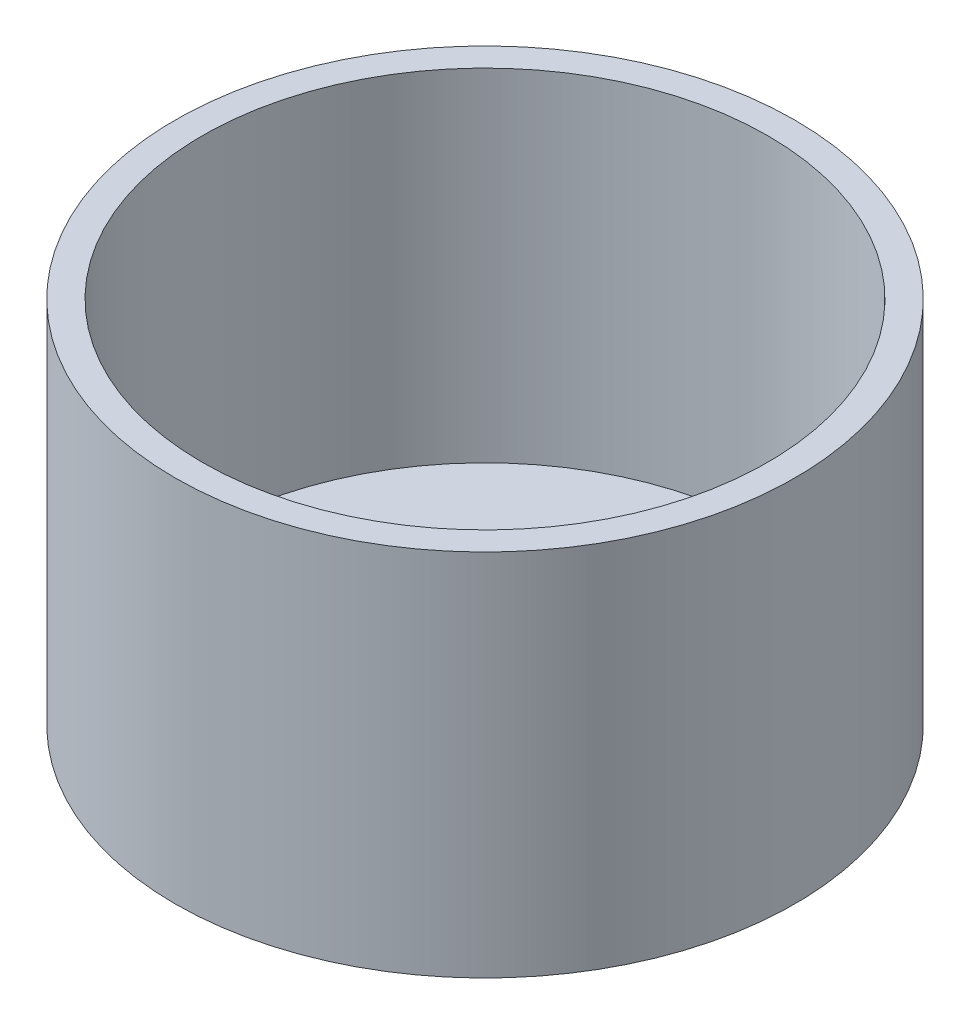
SolidWorks part; units mm, degrees
ref_plane "前视基准面" through (0, 0, 0) normal (0, 0, 1) x (1, 0, 0)
ref_plane "上视基准面" through (0, 0, 0) normal (0, 1, 0) x (1, 0, 0)
ref_plane "右视基准面" through (0, 0, 0) normal (1, 0, 0) x (0, 0, -1)
sketch "草图1" plane through (0, 0, 0) normal (0, 0, 1) x (1, 0, 0)
  line L0 (0, 0) -> (25.2, 0)
  line L1 (25.2, 0) -> (25.2, 30)
  line L2 (0, 2.2) -> (23, 2.2)
  line L3 (23, 2.2) -> (23, 30)
  line L4 (23, 30) -> (25.2, 30)
  line L5 (0, 2.2) -> (0, 0)
  dimension "D2" = 23
  dimension "D3" = 30
  dimension "D1" = 2.2
revolve "旋转1" add sketch "草图1" angle 360 about L5
sketch "草图2" plane through (0, 0, 0) normal (0, -1, 0) x (1, 0, 0)
  circle A0 centre (0, 0) radius 2.2
  circle A1 centre (0, 0) radius 8.5 construction
  circle A2 centre (8.5, 0) radius 1.55
  dimension "D1" = 4.4
  dimension "D2" = 17
  dimension "D3" = 3.1
extrude "切除-拉伸1" cut sketch "草图2" against normal through all
pattern_circular "阵列(圆周)1" count 4 over 360 about axis through (0, 0, 0) along (0, 1, 0) of "切除-拉伸1"
